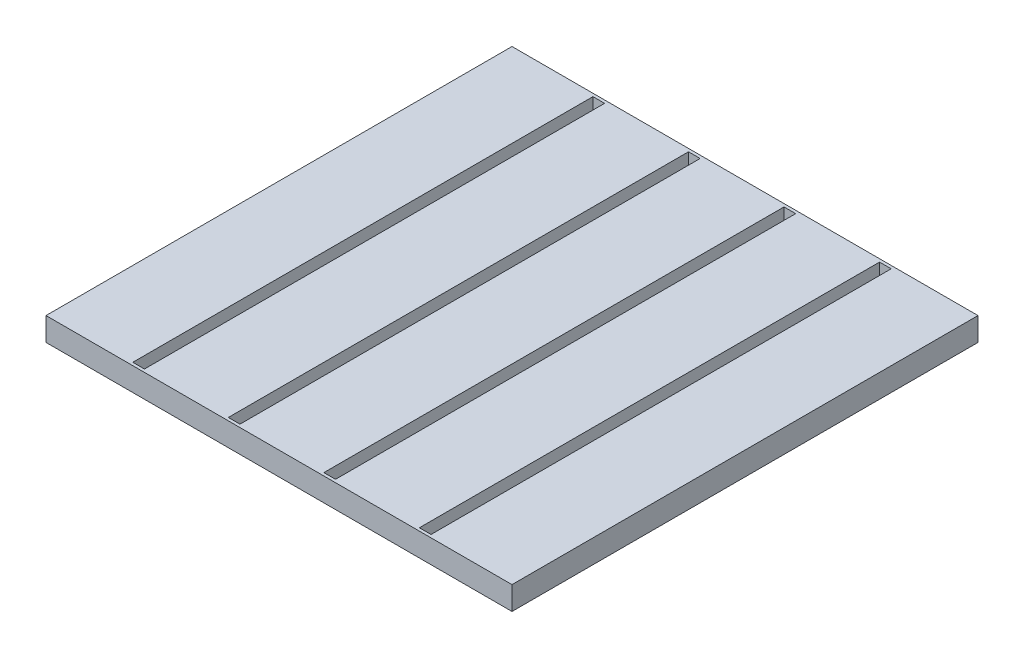
SolidWorks part; units mm, degrees
ref_plane "Front Plane" through (0, 0, 0) normal (0, 0, 1) x (1, 0, 0)
ref_plane "Top Plane" through (0, 0, 0) normal (0, 1, 0) x (1, 0, 0)
ref_plane "Right Plane" through (0, 0, 0) normal (1, 0, 0) x (0, 0, -1)
sketch "Sketch1" plane through (0, 0, 0) normal (0, 1, 0) x (1, 0, 0)
  line L1 (0, 0) -> (40, 0)
  line L2 (0, 0) -> (0, -40)
  line L3 (0, -40) -> (40, -40)
  line L4 (40, 0) -> (40, -40)
  dimension "D1" = 40
  dimension "D2" = 40
extrude "Boss-Extrude1" add sketch "Sketch1" along normal blind 2
sketch "Sketch2" plane through (0, 2, 0) normal (0, 1, 0) x (1, 0, 0)
  line L0 (0, -40) -> (40, -40) construction
  line L3 (0, -40) -> (7.2, -40)
  line L5 (40, 0) -> (0, 0) construction
  line L10 (0, 0) -> (0, -40) construction
  line L11 (7.2, -0.25) -> (8.2, -0.25)
  line L12 (7.2, -0.25) -> (7.2, -39.75)
  line L13 (7.2, -39.75) -> (8.2, -39.75)
  line L14 (8.2, -0.25) -> (8.2, -39.75)
  line L16 (15.4, -0.25) -> (16.4, -0.25)
  line L17 (15.4, -0.25) -> (15.4, -39.75)
  line L18 (15.4, -39.75) -> (16.4, -39.75)
  line L19 (16.4, -0.25) -> (16.4, -39.75)
  line L20 (40, -40) -> (40, 0) construction
  line L21 (23.6, -0.25) -> (24.6, -0.25)
  line L22 (23.6, -0.25) -> (23.6, -39.75)
  line L23 (23.6, -39.75) -> (24.6, -39.75)
  line L24 (24.6, -0.25) -> (24.6, -39.75)
  line L25 (31.8, -0.25) -> (32.8, -0.25)
  line L26 (31.8, -0.25) -> (31.8, -39.75)
  line L27 (31.8, -39.75) -> (32.8, -39.75)
  line L28 (32.8, -0.25) -> (32.8, -39.75)
  dimension "D1" = 7.2
  dimension "D2" = 0.25
  dimension "D3" = 1
  dimension "D4" = 0.25
  dimension "D5" = 1
  dimension "D6" = 7.2
  dimension "D7" = 0.25
  dimension "D8" = 0.25
  dimension "D9" = 1
  dimension "D10" = 7.2
  dimension "D11" = 0.25
  dimension "D12" = 7.2
  dimension "D13" = 7.2
  dimension "D14" = 0.25
  dimension "D15" = 0.25
extrude "Cut-Extrude1" cut sketch "Sketch2" against normal through all contours L14 L11 L12 L13 | L19 L18 L17 L16 | L24 L23 L22 L21 | L28 L27 L26 L25
